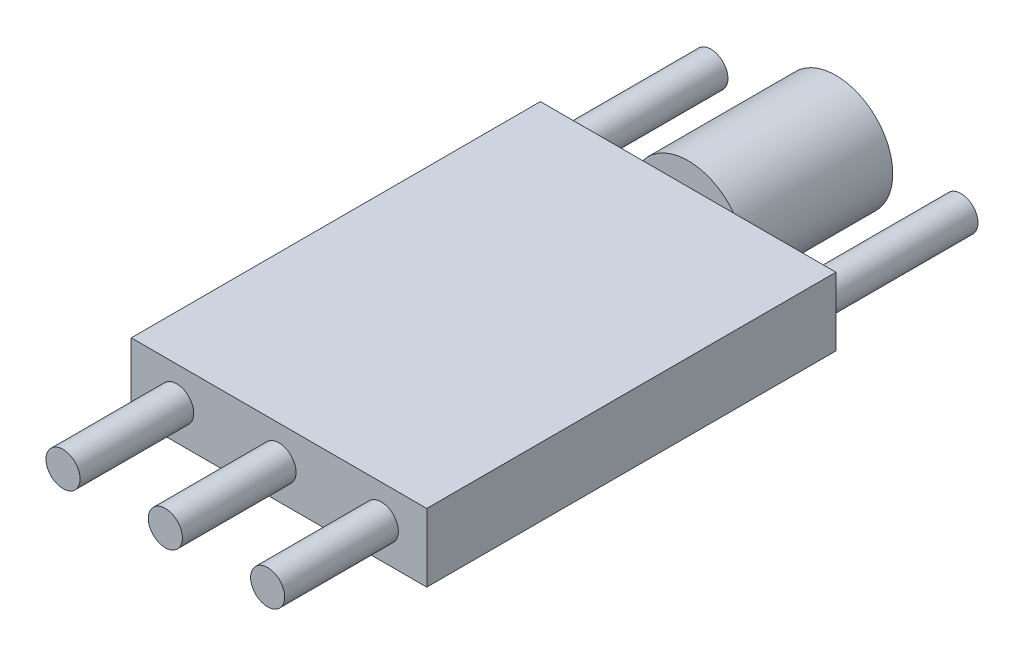
SolidWorks part; units mm, degrees
ref_plane "Front" through (0, 0, 0) normal (0, 0, 1) x (1, 0, 0)
ref_plane "Top" through (0, 0, 0) normal (0, 1, 0) x (1, 0, 0)
ref_plane "Right" through (0, 0, 0) normal (1, 0, 0) x (0, 0, -1)
sketch "Sketch1" plane through (0, 0, 0) normal (0, 1, 0) x (1, 0, 0)
  line L1 (-13, 18) -> (13, 18)
  line L2 (-13, 18) -> (-13, -18)
  line L3 (-13, -18) -> (13, -18)
  line L4 (13, 18) -> (13, -18)
  line L5 (-13, 18) -> (13, -18) construction
  line L6 (-13, -18) -> (13, 18) construction
  point P0 (0, 0)
  dimension "D1" = 26
  dimension "D2" = 36
extrude "Boss-Extrude1" add sketch "Sketch1" along normal blind 6
sketch "Sketch2" plane through (0, 0, 18) normal (0, 0, 1) x (1, 0, 0)
  line L0 (-13, 3) -> (13, 3) construction
  line L1 (-13, 6) -> (-13, 0) construction
  line L2 (13, 6) -> (13, 0) construction
  circle A0 centre (0, 3) radius 1.5
  circle A1 centre (-9, 3) radius 1.5
  circle A2 centre (9, 3) radius 1.5
  dimension "D1" = 3
  dimension "D2" = 3
  dimension "D3" = 3
  dimension "D4" = 9
  dimension "D5" = 9
extrude "Boss-Extrude2" add sketch "Sketch2" along normal blind 10
sketch "Sketch3" plane through (0, 0, -18) normal (0, 0, -1) x (-1, 0, 0)
  line L0 (-13, 3) -> (13, 3) construction
  line L1 (-13, 6) -> (-13, 0) construction
  line L2 (13, 6) -> (13, 0) construction
  circle A0 centre (0, 3) radius 5
  circle A1 centre (-11, 3) radius 1.5
  circle A2 centre (11, 3) radius 1.5
  dimension "D1" = 10
  dimension "D2" = 3
  dimension "D3" = 3
  dimension "D4" = 11
  dimension "D5" = 11
extrude "Boss-Extrude3" add sketch "Sketch3" along normal blind 13
